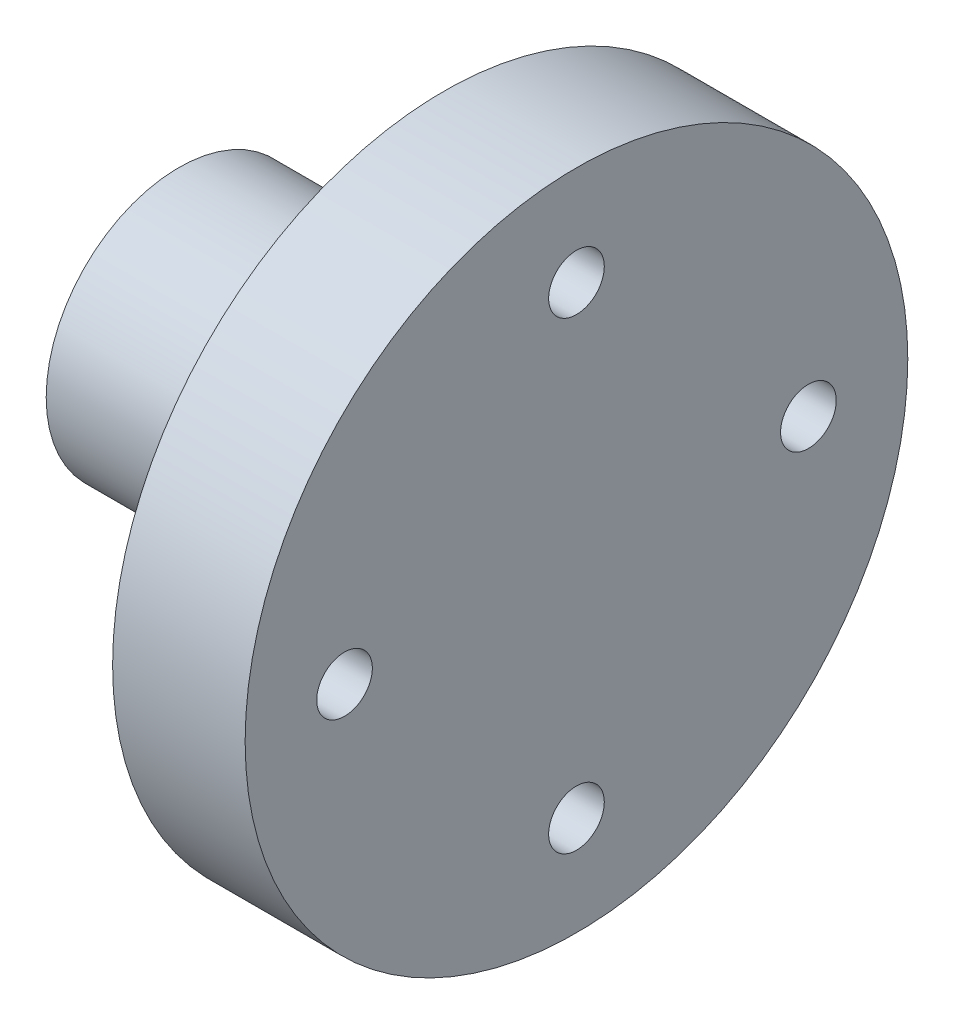
SolidWorks part; units mm, degrees
ref_plane "Front Plane" through (0, 0, 0) normal (0, 0, 1) x (1, 0, 0)
ref_plane "Top Plane" through (0, 0, 0) normal (0, 1, 0) x (1, 0, 0)
ref_plane "Right Plane" through (0, 0, 0) normal (1, 0, 0) x (0, 0, -1)
sketch "Sketch1" plane through (0, 0, 0) normal (0, 1, 0) x (1, 0, 0)
  line L0 (26.6937, 0) -> (56.6937, 0) construction
  line L1 (26.6937, 0) -> (26.6937, 10.0105)
  line L2 (26.6937, 10.0105) -> (46.6937, 10.0105)
  line L3 (46.6937, 10.0105) -> (46.6937, 25)
  line L4 (46.6937, 25) -> (56.6937, 25)
  line L5 (56.6937, 25) -> (56.6937, 0)
  line L6 (26.6937, 0) -> (56.6937, 0)
  dimension "D1" = 10.0105
  dimension "D2" = 20
  dimension "D3" = 10
  dimension "D4" = 25
revolve "Revolve1" add sketch "Sketch1" angle 360 about L0
sketch "Sketch2" plane through (26.6937, 0, 0) normal (-1, 0, 0) x (0, 0, 1)
  line L0 (-1.5, 6.43) -> (1.5, 6.43)
  line L1 (-1.5, 6.43) -> (-1.5, 3.57)
  line L2 (-1.5, 3.57) -> (1.5, 3.57)
  line L3 (1.5, 6.43) -> (1.5, 3.57)
  line L4 (-1.5, 6.43) -> (1.5, 3.57) construction
  line L5 (-1.5, 3.57) -> (1.5, 6.43) construction
  line L6 (0, 0) -> (0, 7.6121) construction
  circle A0 centre (0, 0) radius 5
  point P3 (0, 5)
  point P10 (0, 5)
  dimension "D1" = 10
  dimension "D2" = 3
  dimension "D3" = 2.86
extrude "Cut-Extrude1" cut sketch "Sketch2" against normal blind 20 contours L1 A0 L3 L2 | L3 A0 L1 L2 | A0 L3 L0 L1
sketch "Sketch3" plane through (56.6937, 0, 0) normal (1, 0, 0) x (0, 0, -1)
  circle A0 centre (0, 0) radius 17.5 construction
  circle A1 centre (0, 17.5) radius 2.1
  circle A2 centre (17.5, 0) radius 2.1
  circle A3 centre (0, -17.5) radius 2.1
  circle A4 centre (-17.5, 0) radius 2.1
  dimension "D1" = 35
  dimension "D2" = 4.2
extrude "Cut-Extrude2" cut sketch "Sketch3" against normal blind 10
